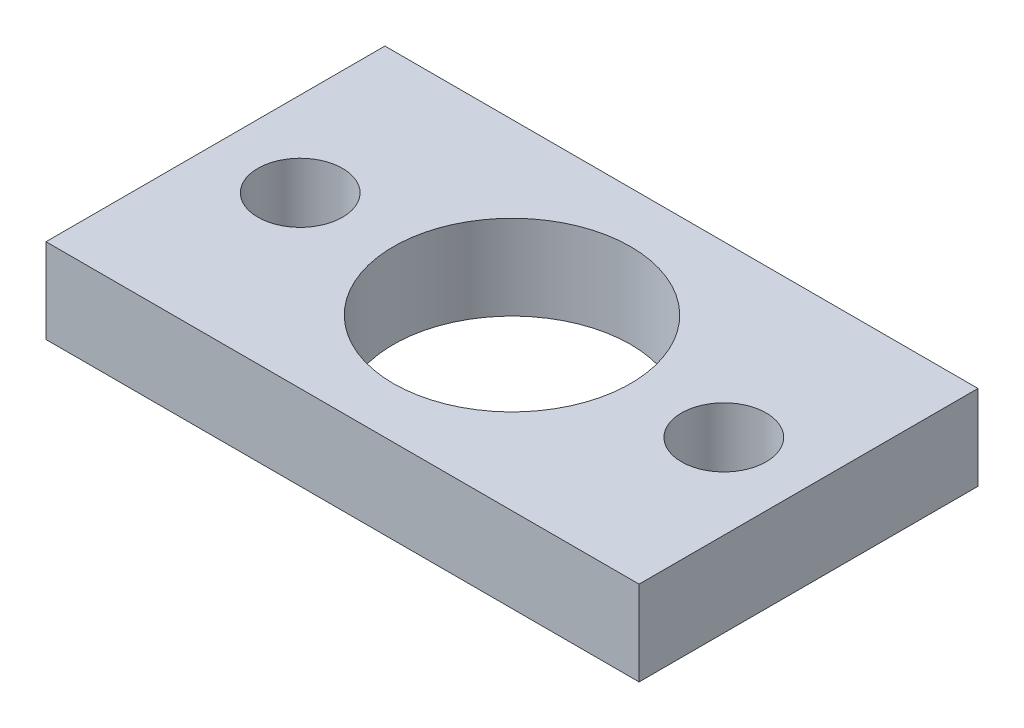
SolidWorks part; units mm, degrees
ref_plane "Front Plane" through (0, 0, 0) normal (0, 0, 1) x (1, 0, 0)
ref_plane "Top Plane" through (0, 0, 0) normal (0, 1, 0) x (1, 0, 0)
ref_plane "Right Plane" through (0, 0, 0) normal (1, 0, 0) x (0, 0, -1)
sketch "Sketch1" plane through (0, 0, 0) normal (0, 1, 0) x (1, 0, 0)
  line L0 (-12.5, 0) -> (12.5, 0) construction
  line L2 (-17.5, -10) -> (17.5, -10)
  line L3 (-17.5, -10) -> (-17.5, 10)
  line L4 (-17.5, 10) -> (17.5, 10)
  line L5 (17.5, -10) -> (17.5, 10)
  line L6 (-17.5, -10) -> (17.5, 10) construction
  line L7 (-17.5, 10) -> (17.5, -10) construction
  circle A0 centre (0, 0) radius 7
  circle A1 centre (12.5, 0) radius 2.5
  circle A2 centre (-12.5, 0) radius 2.5
  dimension "D1" = 14
  dimension "D2" = 5
  dimension "D3" = 25
  dimension "D4" = 35
  dimension "D5" = 20
extrude "Boss-Extrude1" add sketch "Sketch1" along normal mid plane 5
